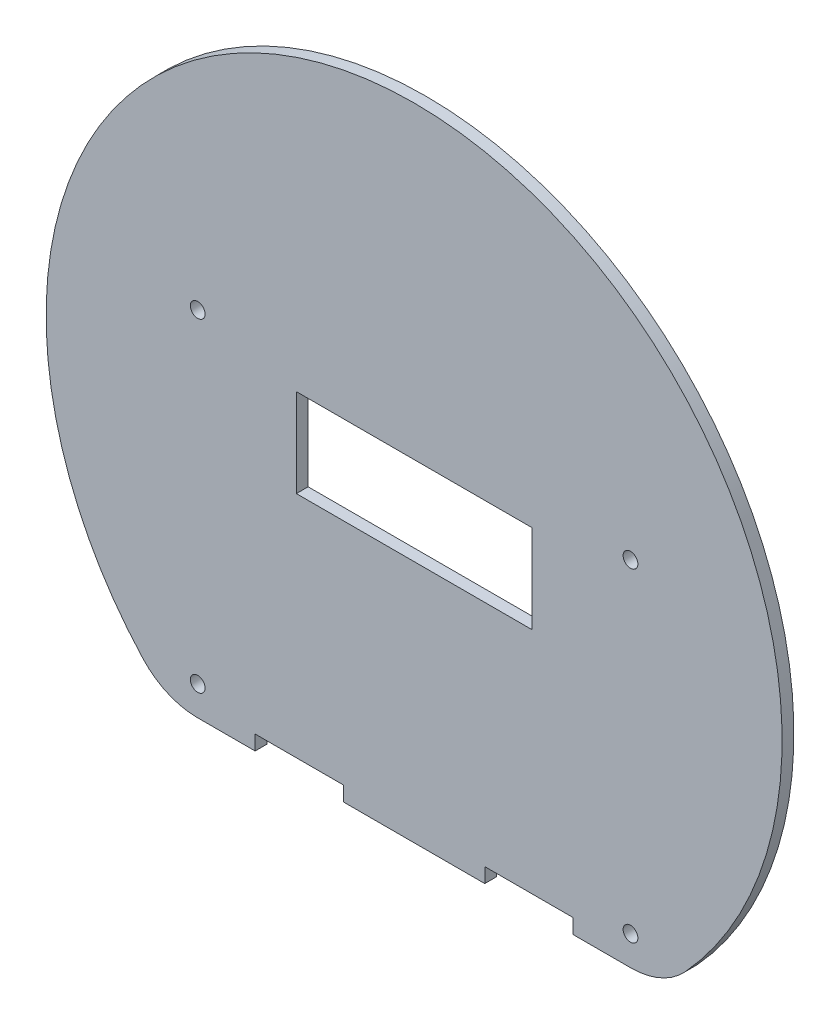
SolidWorks part; units mm, degrees
ref_plane "Front Plane" through (0, 0, 0) normal (0, 0, 1) x (1, 0, 0)
ref_plane "Top Plane" through (0, 0, 0) normal (0, 1, 0) x (1, 0, 0)
ref_plane "Right Plane" through (0, 0, 0) normal (1, 0, 0) x (0, 0, -1)
sketch "Sketch1" plane through (0, 0, 0) normal (0, 0, 1) x (1, 0, 0)
  line L3 (0, 125) -> (0, -125) construction
  circle A4 centre (0, 0) radius 125
  dimension "D1" = 250
extrude "Boss-Extrude1" add sketch "Sketch1" along normal blind 4
sketch "Sketch2" plane through (0, 0, 4) normal (0, 0, 1) x (1, 0, 0)
  circle A0 centre (0, 92.9904) radius 1.5
  circle A1 centre (11.25, 73.5048) radius 1.5
  circle A2 centre (-11.25, 73.5048) radius 1.5
  dimension "D1" = 3
extrude "Cut-Extrude1" [suppressed] cut sketch "Sketch2" against normal blind 10
sketch "Sketch3" plane through (0, 0, 4) normal (0, 0, 1) x (1, 0, 0)
  line L0 (-83.9155, -92.6455) -> (83.9155, -92.6455)
  arc A1 (-83.9155, -92.6455) -> (83.9155, -92.6455) centre (0, 0) ccw
extrude "Cut-Extrude2" cut sketch "Sketch3" against normal blind 10
fillet "Fillet1" radius 25 2 edges at (83.9155, -92.6455, 2) (-83.9155, -92.6455, 2)
sketch "Sketch6" plane through (0, 0, 4) normal (0, 0, 1) x (1, 0, 0)
  line L0 (73.6484, -92.6455) -> (-73.6484, -92.6455) construction
  line L1 (24, -92.6455) -> (54, -92.6455)
  line L2 (24, -92.6455) -> (24, -87.6455)
  line L3 (24, -87.6455) -> (54, -87.6455)
  line L4 (54, -92.6455) -> (54, -87.6455)
  line L5 (0, 0) -> (0, -92.6455) construction
  line L6 (-54, -92.6455) -> (-54, -87.6455)
  line L7 (-24, -87.6455) -> (-54, -87.6455)
  line L8 (-24, -92.6455) -> (-24, -87.6455)
  line L9 (-24, -92.6455) -> (-54, -92.6455)
  arc A0 (92.0605, -84.5568) -> (-92.0605, -84.5568) centre (0, 0) ccw construction
  dimension "D1" = 30
  dimension "D2" = 54
  dimension "D3" = 5
extrude "Cut-Extrude5" cut sketch "Sketch6" against normal blind 5
sketch "Sketch7" plane through (0, 0, 4) normal (0, 0, 1) x (1, 0, 0)
  circle A0 centre (73.5, -82.6455) radius 2.5
  circle A1 centre (73.5, 27.3545) radius 2.5
  circle A2 centre (-73.5, 27.3545) radius 2.5
  circle A3 centre (-73.5, -82.6455) radius 2.5
  dimension "D1" = 5
extrude "Cut-Extrude6" cut sketch "Sketch7" against normal through all
sketch "Sketch8" plane through (0, 0, 4) normal (0, 0, 1) x (1, 0, 0)
  line L1 (-40, 20.0745) -> (40, 20.0745)
  line L2 (-40, 20.0745) -> (-40, -9.9255)
  line L3 (-40, -9.9255) -> (40, -9.9255)
  line L4 (40, 20.0745) -> (40, -9.9255)
  line L5 (-40, 20.0745) -> (40, -9.9255) construction
  line L6 (-40, -9.9255) -> (40, 20.0745) construction
  point P0 (0, 5.0745)
  point P5 (0, -21.489)
  dimension "D1" = 80
  dimension "D2" = 30
extrude "Cut-Extrude7" cut sketch "Sketch8" against normal through all
